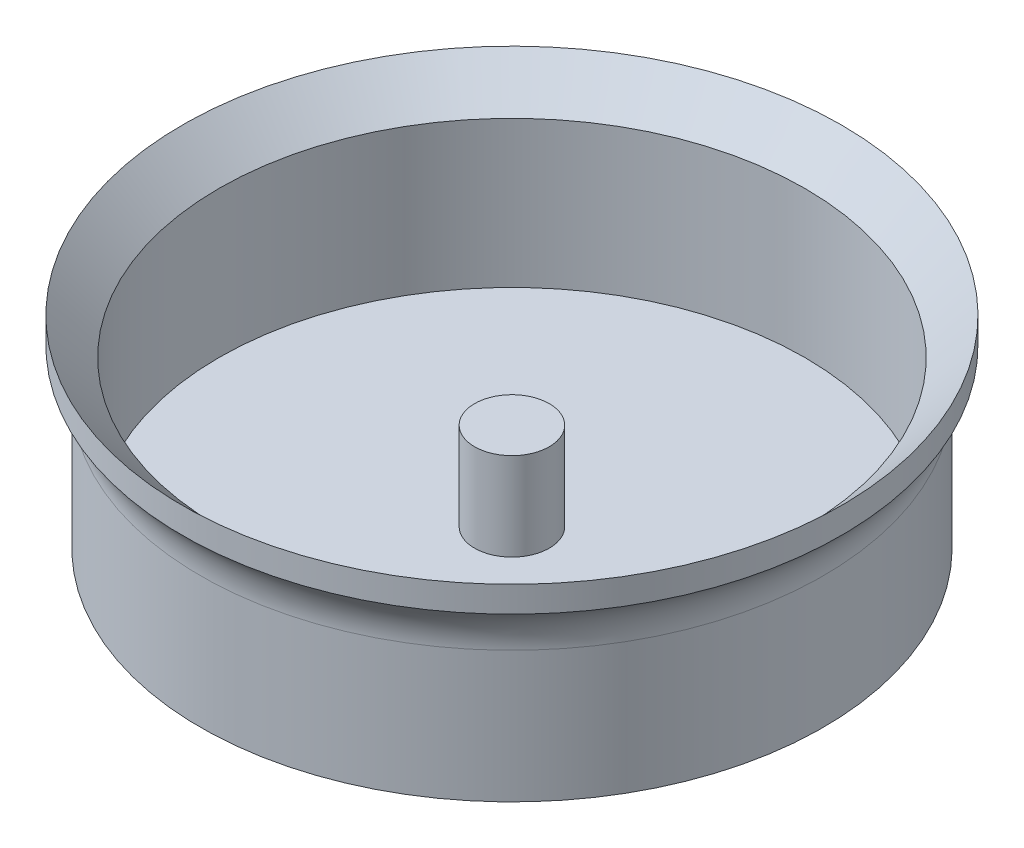
SolidWorks part; units mm, degrees
ref_plane "Front Plane" through (0, 0, 0) normal (0, 0, 1) x (1, 0, 0)
ref_plane "Top Plane" through (0, 0, 0) normal (0, 1, 0) x (1, 0, 0)
ref_plane "Right Plane" through (0, 0, 0) normal (1, 0, 0) x (0, 0, -1)
sketch "Sketch2" plane through (0, 0, 0) normal (1, 0, 0) x (0, 0, -1)
  line L0 (0, 0) -> (0, -6.0614) construction
  line L1 (0, 0) -> (0, 9.2075)
  line L2 (0, 9.2075) -> (3.2385, 9.2075)
  line L3 (3.2385, 9.2075) -> (3.2385, 1.5875)
  line L4 (3.2385, 1.5875) -> (25.4, 1.5875)
  line L5 (25.4, 1.5875) -> (25.4, 14.2875)
  line L6 (25.4, 14.2875) -> (28.575, 17.4625)
  line L7 (28.575, 17.4625) -> (28.575, 15.2174)
  line L9 (26.9875, 11.3849) -> (26.9875, 0)
  line L10 (26.9875, 0) -> (0, 0)
  line L11 (28.575, 15.2174) -> (24.5305, 11.173) construction
  arc A0 (28.575, 15.2174) -> (26.9875, 11.3849) centre (32.4076, 11.3849) ccw
  point P11 (26.9875, 18.8122)
  point P13 (28.575, 22.6212)
  dimension "D1" = 1.5875
  dimension "D2" = 1.5875
  dimension "D3" = 50.8
  dimension "D4" = 6.477
  dimension "D5" = 7.62
  dimension "D6" = 12.7
  dimension "D7" = 1.5875
  dimension "D8" = 3.175
  dimension "D9" = 45
revolve "Revolve1" add sketch "Sketch2" angle 360 about L1
